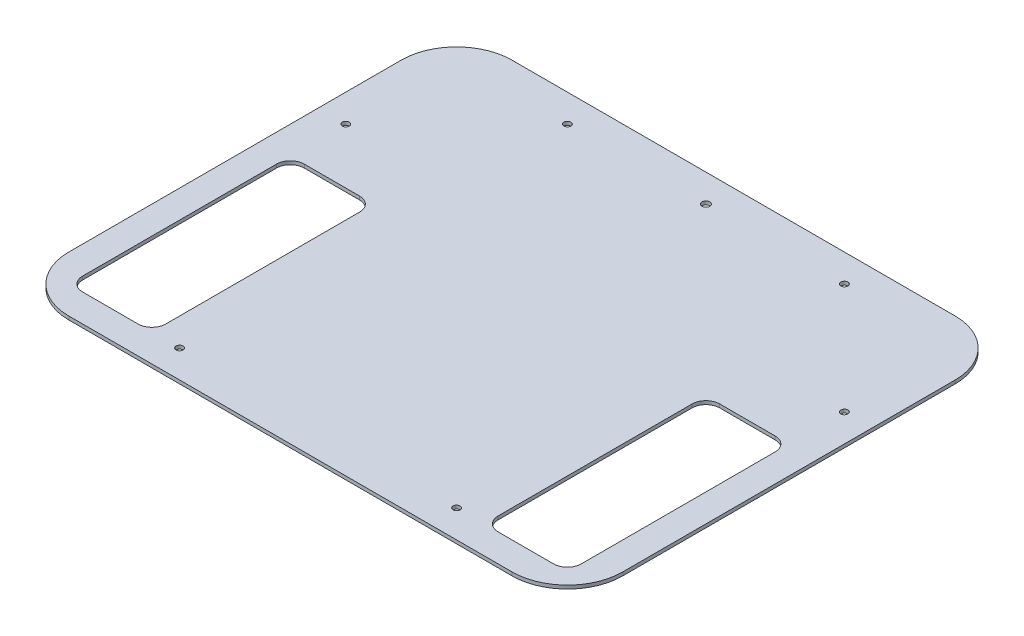
SolidWorks part; units mm, degrees
ref_plane "Front Plane" through (0, 0, 0) normal (0, 0, 1) x (1, 0, 0)
ref_plane "Top Plane" through (0, 0, 0) normal (0, 1, 0) x (1, 0, 0)
ref_plane "Right Plane" through (0, 0, 0) normal (1, 0, 0) x (0, 0, -1)
sketch "Sketch1" plane through (0, 0, 0) normal (0, 1, 0) x (1, 0, 0)
  line L0 (-254, 203.2) -> (254, -203.2) construction
  line L1 (-254, 203.2) -> (254, 203.2)
  line L2 (-254, 203.2) -> (-254, -203.2)
  line L3 (-254, -203.2) -> (254, -203.2)
  line L4 (254, 203.2) -> (254, -203.2)
  point P4 (0, 0)
  dimension "D1" = 508
  dimension "D2" = 406.4
extrude "Extrude1" add sketch "Sketch1" along normal blind 3.175
sketch "Sketch2" plane through (0, 3.175, 0) normal (0, 1, 0) x (1, 0, 0)
  line L0 (-152.4, 0) -> (152.4, 0) construction
  line L1 (-228.6, -177.8) -> (-152.4, -177.8)
  line L2 (-228.6, -177.8) -> (-228.6, 25.4)
  line L3 (-228.6, 25.4) -> (-152.4, 25.4)
  line L4 (-152.4, -177.8) -> (-152.4, 25.4)
  line L5 (152.4, -177.8) -> (228.6, -177.8)
  line L6 (152.4, -177.8) -> (152.4, 25.4)
  line L7 (152.4, 25.4) -> (228.6, 25.4)
  line L8 (228.6, -177.8) -> (228.6, 25.4)
  line L9 (-254, -203.2) -> (254, -203.2) construction
  line L10 (-254, 203.2) -> (-254, -203.2) construction
  point P10 (0, 0)
  dimension "D1" = 203.2
  dimension "D2" = 203.2
  dimension "D3" = 76.2
  dimension "D4" = 76.2
  dimension "D5" = 25.4
  dimension "D6" = 25.4
extrude "Extrude2" cut sketch "Sketch2" against normal through all
fillet "Fillet2" radius 50.8 4 edges at (-254, 1.5875, -203.2) (254, 1.5875, -203.2) (254, 1.5875, 203.2) (-254, 1.5875, 203.2)
fillet "Fillet3" radius 12.7 8 edges at (-152.4, 1.5875, -25.4) (-228.6, 1.5875, -25.4) (-152.4, 1.5875, 177.8) (-228.6, 1.5875, 177.8) (228.6, 1.5875, -25.4) (152.4, 1.5875, -25.4) (152.4, 1.5875, 177.8) (228.6, 1.5875, 177.8)
hole_wizard "1/4 (0.25) Diameter Hole1" positions "Sketch4" profile "Sketch3" hole size "1/4" standard "Ansi Inch"
sketch "Sketch4" plane through (0, 3.175, 0) normal (0, 1, 0) x (-1, 0, 0)
  line L0 (254, -152.4) -> (254, 152.4) construction
  line L1 (-254, 152.4) -> (-254, -152.4) construction
  line L2 (-203.2, -203.2) -> (203.2, -203.2) construction
  line L3 (203.2, 203.2) -> (-203.2, 203.2) construction
  point P0 (127, -177.8)
  point P1 (-127, -177.8)
  point P3 (-228.6, -76.2)
  point P5 (228.6, -76.2)
  point P7 (127, 177.8)
  point P9 (-127, 177.8)
  dimension "D1" = 127
  dimension "D2" = 127
  dimension "D3" = 127
  dimension "D4" = 25.4
  dimension "D5" = 25.4
  dimension "D6" = 25.4
  dimension "D7" = 25.4
sketch "Sketch3" plane through (-127, 3.175, -177.8) normal (1, 0, 0) x (0, 0, 1)
  line L0 (0, 0) -> (0, 27.3077)
  line L1 (0, 27.3077) -> (3.175, 25.4)
  line L2 (3.175, 25.4) -> (3.175, 0)
  line L5 (3.175, 0) -> (0, 0)
  line L10 (0, 27.3077) -> (-3.175, 25.4) construction
  line L11 (0, -6.35) -> (0, 107.95) construction
  dimension "Hole Dia." = 6.35
  dimension "Hole Depth" = 25.4
  dimension "Drill Angle" = 118
sketch "Sketch5" plane through (0, 3.175, 0) normal (0, 1, 0) x (1, 0, 0)
  line L0 (203.2, 203.2) -> (-203.2, 203.2) construction
  circle A0 centre (0, 177.8) radius 3.5784
  dimension "D1" = 25.4
extrude "Cut-Extrude1" cut sketch "Sketch5" against normal up to next
